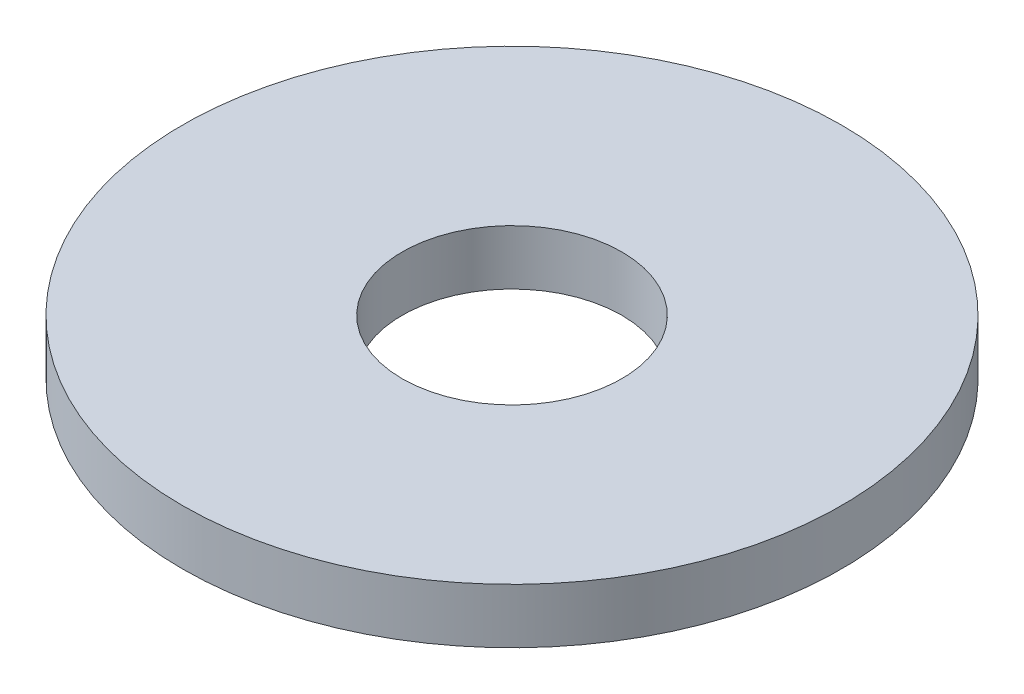
SolidWorks part; units mm, degrees
material "不锈钢 (铁素体)"
ref_plane "前视基准面" through (0, 0, 0) normal (0, 0, 1) x (1, 0, 0)
ref_plane "上视基准面" through (0, 0, 0) normal (0, 1, 0) x (1, 0, 0)
ref_plane "右视基准面" through (0, 0, 0) normal (1, 0, 0) x (0, 0, -1)
sketch "草图1" plane through (0, 0, 0) normal (0, 1, 0) x (1, 0, 0)
  circle A0 centre (0, 0) radius 2
  circle A1 centre (0, 0) radius 6
  dimension "D1" = 4
  dimension "D2" = 12
extrude "凸台-拉伸1" add sketch "草图1" along normal blind 1
